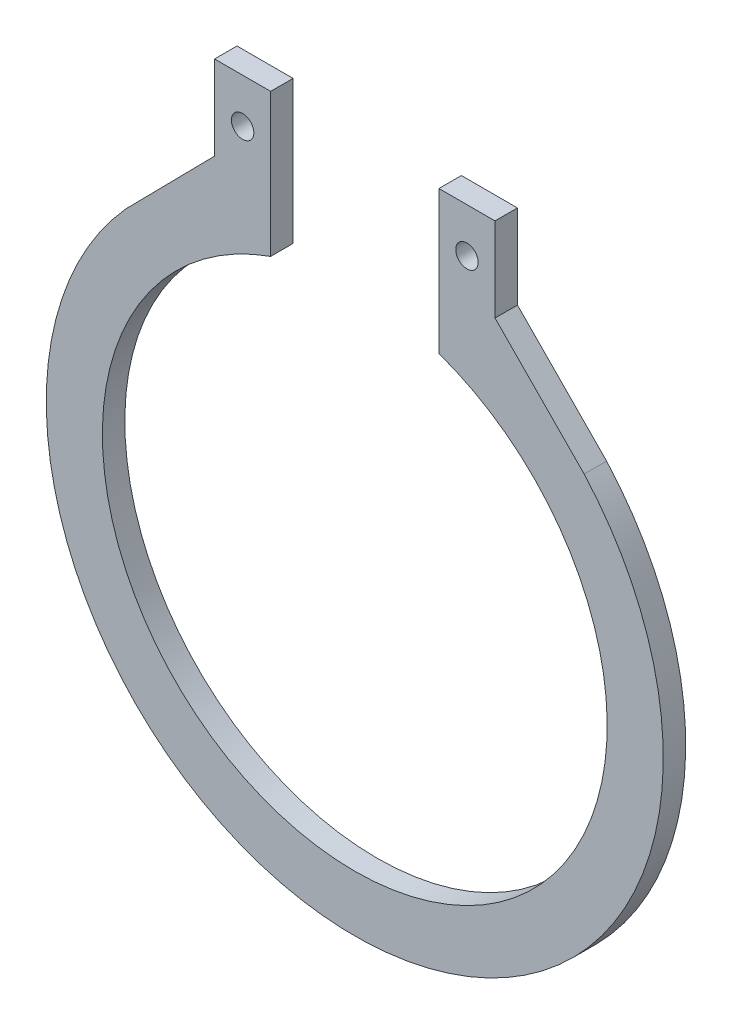
SolidWorks part; units mm, degrees
ref_plane "Front Plane" through (0, 0, 0) normal (0, 0, 1) x (1, 0, 0)
ref_plane "Top Plane" through (0, 0, 0) normal (0, 1, 0) x (1, 0, 0)
ref_plane "Right Plane" through (0, 0, 0) normal (1, 0, 0) x (0, 0, -1)
sketch "Sketch1" plane through (0, 0, 0) normal (0, 0, 1) x (1, 0, 0)
  line L1 (-12.5, 26.4575) -> (-20.4467, 18.3897)
  line L2 (-12.5, 33.9575) -> (-7.5, 33.9575)
  line L3 (-7.5, 21.2132) -> (-7.5, 33.9575)
  line L4 (-12.5, 33.9575) -> (-7.5, 33.9575)
  line L5 (-12.5, 26.4575) -> (-12.5, 33.9575)
  line L7 (7.5, 21.2132) -> (7.5, 33.9575)
  line L8 (7.5, 33.9575) -> (12.5, 33.9575)
  line L9 (12.5, 26.4575) -> (12.5, 33.9575)
  line L10 (12.5, 26.4575) -> (20.4467, 18.3897)
  arc A0 (-7.5, 21.2132) -> (7.5, 21.2132) centre (0, 0) ccw
  arc A1 (-18.6968, 20.1663) -> (18.6968, 20.1663) centre (0, 0) ccw
  circle A5 centre (-10, 30) radius 1
  circle A6 centre (10, 30) radius 1
  dimension "D1" = 45
  dimension "D3" = 2
  dimension "D4" = 2
  dimension "D7" = 30
  dimension "D9" = 5
  dimension "D10" = 7.5
  dimension "D11" = 7.5
  dimension "D13" = 5
  dimension "D2" = 5
extrude "Extrude1" add sketch "Sketch1" along normal blind 2
